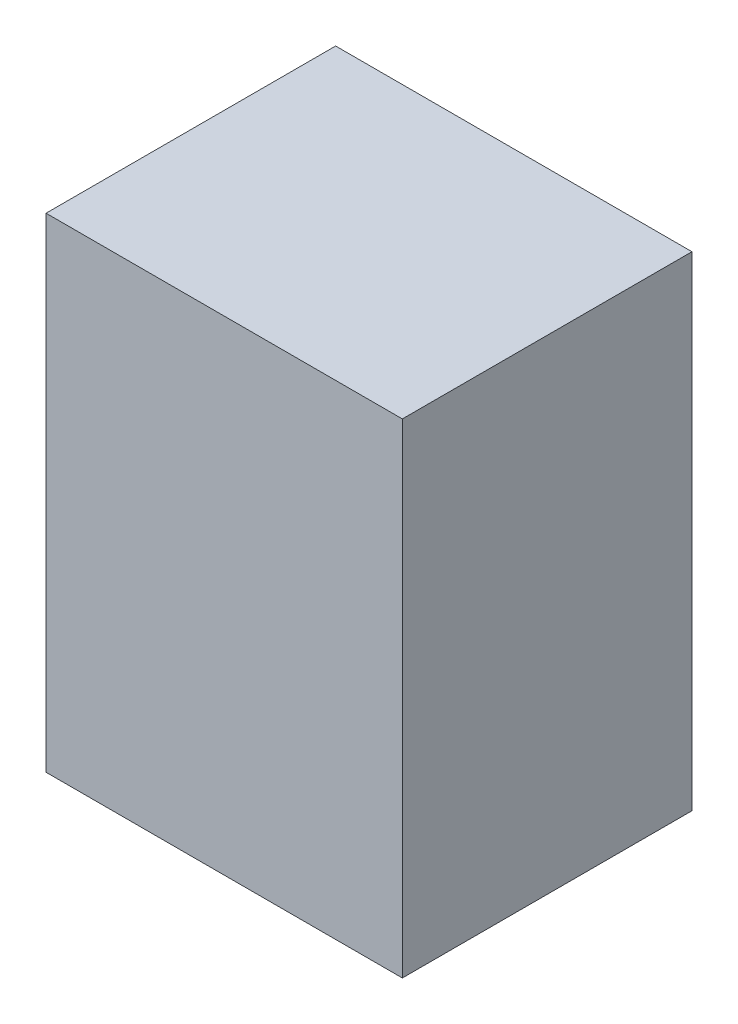
SolidWorks part; units mm, degrees
ref_plane "Front Plane" through (0, 0, 0) normal (0, 0, 1) x (1, 0, 0)
ref_plane "Top Plane" through (0, 0, 0) normal (0, 1, 0) x (1, 0, 0)
ref_plane "Right Plane" through (0, 0, 0) normal (1, 0, 0) x (0, 0, -1)
sketch "Sketch1" plane through (0, 0, 0) normal (0, 0, 1) x (1, 0, 0)
  line L0 (7.6645, -65.25) -> (16.9845, -65.25) construction
  line L1 (7.8645, -65.45) -> (16.7845, -65.45)
  line L2 (7.8645, -65.45) -> (7.8645, -77.5714)
  line L3 (7.8645, -77.5714) -> (16.7845, -77.5714)
  line L4 (16.7845, -65.45) -> (16.7845, -77.5714)
  line L5 (16.9845, -65.25) -> (16.9845, -77.7714) construction
  line L6 (7.6645, -77.7714) -> (16.9845, -77.7714) construction
  line L7 (7.6645, -77.7714) -> (7.6645, -65.25) construction
  dimension "D1" = 0.2
  dimension "D2" = 0.2
  dimension "D3" = 0.2
  dimension "D4" = 0.2
extrude "Boss-Extrude1" add sketch "Sketch1" along normal blind 7.25
shell "Shell1" thickness 0.5
equation "\"D2@Sketch1\"=\"D1@Sketch1\""
equation "\"D3@Sketch1\"=\"D1@Sketch1\""
equation "\"D4@Sketch1\"=\"D1@Sketch1\""
